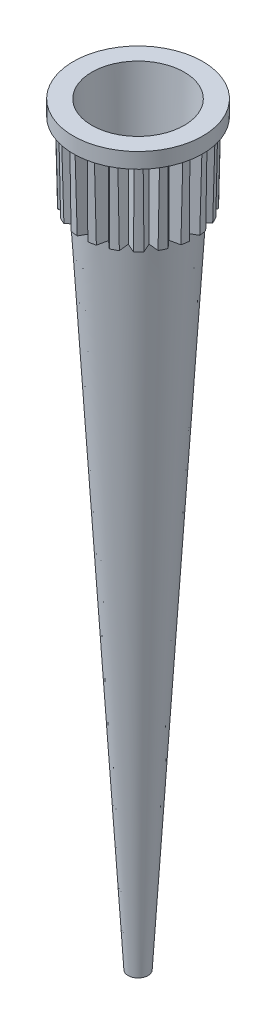
SolidWorks part; units mm, degrees
ref_plane "Ön Düzlem" through (0, 0, 0) normal (0, 0, 1) x (1, 0, 0)
ref_plane "Üst Düzlem" through (0, 0, 0) normal (0, 1, 0) x (1, 0, 0)
ref_plane "Sağ Düzlem" through (0, 0, 0) normal (1, 0, 0) x (0, 0, -1)
sketch "Çizim1" plane through (0, 0, 0) normal (0, 0, 1) x (1, 0, 0)
  line L0 (0, 0) -> (0, 49)
  line L1 (0, 49) -> (4.2, 49)
  line L2 (4.2, 49) -> (4.2, 48)
  line L3 (4.2, 48) -> (3.8, 48)
  line L4 (3.8, 48) -> (3.7, 43)
  line L5 (3.7, 43) -> (3.15, 43)
  line L7 (3.15, 43) -> (0.65, 0)
  line L8 (0.65, 0) -> (0, 0)
  dimension "D1" = 49
  dimension "D2" = 1
  dimension "D3" = 3.8
  dimension "D4" = 5
  dimension "D5" = 3.15
  dimension "D6" = 0.65
  dimension "D7" = 4.2
  dimension "D8" = 3.7
  dimension "D9" = 43
revolve "Döndür1" add sketch "Çizim1" angle 360 about L0
sketch "Çizim2" plane through (0, 49, 0) normal (0, 1, 0) x (1, 0, 0)
  circle A0 centre (0, 0) radius 3
  dimension "D1" = 6
extrude "Kes-Ekstrüzyon1" cut sketch "Çizim2" against normal up to surface (49 mm away) draft 3
sketch "Çizim3" plane through (0, 43, 0) normal (0, -1, 0) x (1, 0, 0)
  line L0 (0.0822, 3.1) -> (-0.4178, 3.966)
  line L1 (-0.4178, 3.966) -> (0.5822, 3.966)
  line L2 (0.5822, 3.966) -> (0.0822, 3.1)
  line L3 (0.8153, 3.9189) -> (1.7663, 3.6099)
  line L4 (1.0232, 2.9408) -> (0.8153, 3.9189)
  line L5 (1.7663, 3.6099) -> (1.0232, 2.9408)
  line L6 (1.9734, 3.4931) -> (2.7824, 2.9053)
  line L7 (1.8688, 2.4985) -> (1.9734, 3.4931)
  line L8 (2.7824, 2.9053) -> (1.8688, 2.4985)
  line L9 (2.9432, 2.7302) -> (3.531, 1.9212)
  line L10 (2.5365, 1.8167) -> (2.9432, 2.7302)
  line L11 (3.531, 1.9212) -> (2.5365, 1.8167)
  line L12 (3.6298, 1.705) -> (3.9388, 0.7539)
  line L13 (2.9607, 0.9618) -> (3.6298, 1.705)
  line L14 (3.9388, 0.7539) -> (2.9607, 0.9618)
  line L15 (3.966, 0.5178) -> (3.966, -0.4822)
  line L16 (3.1, 0.0178) -> (3.966, 0.5178)
  line L17 (3.966, -0.4822) -> (3.1, 0.0178)
  line L18 (3.9189, -0.7153) -> (3.6099, -1.6663)
  line L19 (2.9408, -0.9232) -> (3.9189, -0.7153)
  line L20 (3.6099, -1.6663) -> (2.9408, -0.9232)
  line L21 (3.4931, -1.8734) -> (2.9053, -2.6824)
  line L22 (2.4985, -1.7688) -> (3.4931, -1.8734)
  line L23 (2.9053, -2.6824) -> (2.4985, -1.7688)
  line L24 (2.7302, -2.8432) -> (1.9212, -3.431)
  line L25 (1.8167, -2.4365) -> (2.7302, -2.8432)
  line L26 (1.9212, -3.431) -> (1.8167, -2.4365)
  line L27 (1.705, -3.5298) -> (0.7539, -3.8388)
  line L28 (0.9618, -2.8607) -> (1.705, -3.5298)
  line L29 (0.7539, -3.8388) -> (0.9618, -2.8607)
  line L30 (0.5178, -3.866) -> (-0.4822, -3.866)
  line L31 (0.0178, -3) -> (0.5178, -3.866)
  line L32 (-0.4822, -3.866) -> (0.0178, -3)
  line L33 (-0.7153, -3.8189) -> (-1.6663, -3.5099)
  line L34 (-0.9232, -2.8408) -> (-0.7153, -3.8189)
  line L35 (-1.6663, -3.5099) -> (-0.9232, -2.8408)
  line L36 (-1.8734, -3.3931) -> (-2.6824, -2.8053)
  line L37 (-1.7688, -2.3985) -> (-1.8734, -3.3931)
  line L38 (-2.6824, -2.8053) -> (-1.7688, -2.3985)
  line L39 (-2.8432, -2.6302) -> (-3.431, -1.8212)
  line L40 (-2.4365, -1.7167) -> (-2.8432, -2.6302)
  line L41 (-3.431, -1.8212) -> (-2.4365, -1.7167)
  line L42 (-3.5298, -1.605) -> (-3.8388, -0.6539)
  line L43 (-2.8607, -0.8618) -> (-3.5298, -1.605)
  line L44 (-3.8388, -0.6539) -> (-2.8607, -0.8618)
  line L45 (-3.866, -0.4178) -> (-3.866, 0.5822)
  line L46 (-3, 0.0822) -> (-3.866, -0.4178)
  line L47 (-3.866, 0.5822) -> (-3, 0.0822)
  line L48 (-3.8189, 0.8153) -> (-3.5099, 1.7663)
  line L49 (-2.8408, 1.0232) -> (-3.8189, 0.8153)
  line L50 (-3.5099, 1.7663) -> (-2.8408, 1.0232)
  line L51 (-3.3931, 1.9734) -> (-2.8053, 2.7824)
  line L52 (-2.3985, 1.8688) -> (-3.3931, 1.9734)
  line L53 (-2.8053, 2.7824) -> (-2.3985, 1.8688)
  line L54 (-2.6302, 2.9432) -> (-1.8212, 3.531)
  line L55 (-1.7167, 2.5365) -> (-2.6302, 2.9432)
  line L56 (-1.8212, 3.531) -> (-1.7167, 2.5365)
  line L57 (-1.605, 3.6298) -> (-0.6539, 3.9388)
  line L58 (-0.8618, 2.9607) -> (-1.605, 3.6298)
  line L59 (-0.6539, 3.9388) -> (-0.8618, 2.9607)
  point P63 (0.05, 0.05)
  dimension "D1" = 60
  dimension "D2" = 60
  dimension "D3" = 1
  dimension "D4" = 3.1
extrude "Kes-Ekstrüzyon4" cut sketch "Çizim3" against normal blind 5
